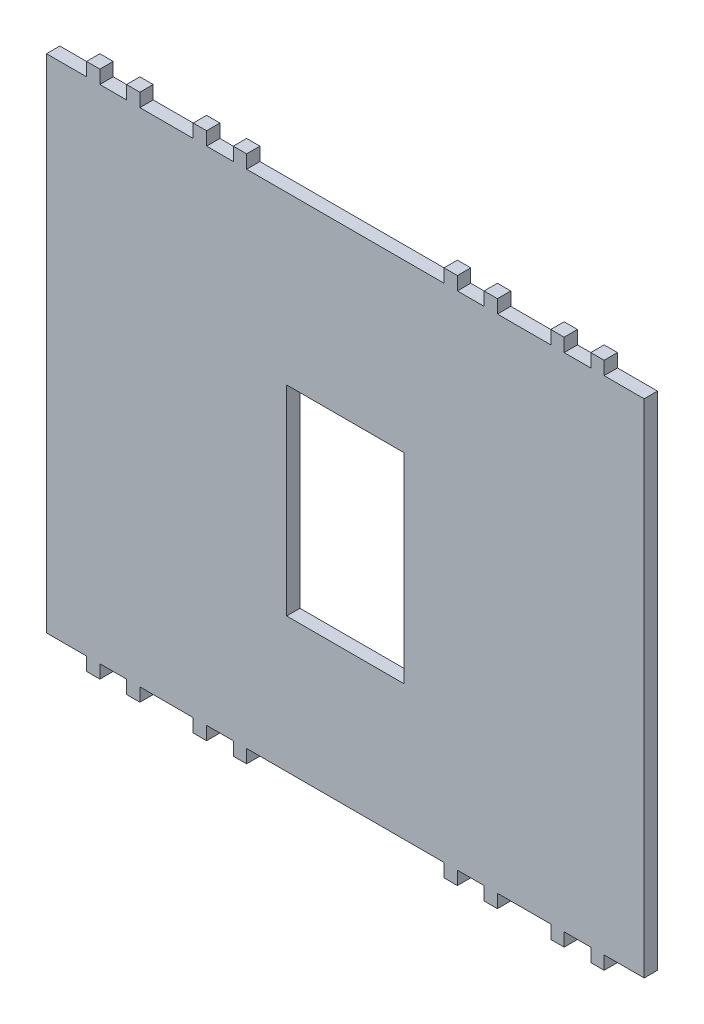
SolidWorks part; units mm, degrees
ref_plane "Plan de face" through (0, 0, 0) normal (0, 0, 1) x (1, 0, 0)
ref_plane "Plan de dessus" through (0, 0, 0) normal (0, 1, 0) x (1, 0, 0)
ref_plane "Plan de droite" through (0, 0, 0) normal (1, 0, 0) x (0, 0, -1)
sketch "Esquisse1" plane through (0, 0, 0) normal (0, 0, 1) x (1, 0, 0)
  line L0 (0, 0) -> (0, 94) construction
  line L1 (-21.3539, 94) -> (28.0805, 94) construction
  line L2 (-30, 188) -> (-45, 188)
  line L3 (-45, 188) -> (-45, 0) construction
  line L4 (-45, 0) -> (-30, 0)
  line L5 (-10, 0) -> (10, 0)
  line L6 (30, 0) -> (45, 0)
  line L7 (45, 0) -> (45, 188)
  line L8 (45, 188) -> (30, 188)
  line L9 (10, 188) -> (-10, 188)
  line L10 (-45, 188) -> (-45, 125.5) construction
  line L11 (-45, 125.5) -> (-89, 125.5)
  line L12 (-67, 125.5) -> (-67, 50.5) construction
  line L13 (-67, 50.5) -> (-45, 50.5)
  line L14 (-45, 50.5) -> (-45, 0) construction
  line L15 (-67, 50.5) -> (-89, 50.5)
  line L16 (-89, 50.5) -> (-89, 0) construction
  line L17 (-89, 0) -> (-104, 0)
  line L18 (-124, 0) -> (-144, 0)
  line L19 (-164, 0) -> (-179, 0)
  line L20 (-179, 0) -> (-179, 188)
  line L21 (-179, 188) -> (-164, 188)
  line L22 (-144, 188) -> (-124, 188)
  line L23 (-89, 188) -> (-89, 125.5) construction
  line L24 (-104, 188) -> (-89, 188)
  line L25 (-179, 0) -> (-179, 188) construction
  line L26 (-179, 0) -> (-174, 0) construction
  line L27 (-89, 125.5) -> (-89, 50.5)
  line L28 (-45, 50.5) -> (-45, 125.5)
  line L29 (-89, 188) -> (-45, 188)
  line L30 (-89, 0) -> (-45, 0)
  line B0 (-20, 0) -> (-20, 11.1075) construction
  line B1 (-20, 0) -> (-25, 0)
  line B2 (-25, -5) -> (-30, -5)
  line B3 (-30, -5) -> (-30, 0)
  line B4 (-25, -5) -> (-25, 0)
  line B5 (-20, 0) -> (-15, 0)
  line B6 (-15, 0) -> (-15, -5)
  line B7 (-15, -5) -> (-10, -5)
  line B8 (-10, -5) -> (-10, 0)
  line B9 (20, 0) -> (20, 11.1075) construction
  line B10 (20, 0) -> (25, 0)
  line B11 (25, -5) -> (30, -5)
  line B12 (30, -5) -> (30, 0)
  line B13 (25, -5) -> (25, 0)
  line B14 (20, 0) -> (15, 0)
  line B15 (15, 0) -> (15, -5)
  line B16 (15, -5) -> (10, -5)
  line B17 (10, -5) -> (10, 0)
  line B18 (20, 188) -> (20, 176.8925) construction
  line B19 (20, 188) -> (25, 188)
  line B20 (25, 193) -> (30, 193)
  line B21 (30, 193) -> (30, 188)
  line B22 (25, 193) -> (25, 188)
  line B23 (20, 188) -> (15, 188)
  line B24 (15, 188) -> (15, 193)
  line B25 (15, 193) -> (10, 193)
  line B26 (10, 193) -> (10, 188)
  line B27 (-20, 188) -> (-20, 176.8925) construction
  line B28 (-20, 188) -> (-25, 188)
  line B29 (-25, 193) -> (-30, 193)
  line B30 (-30, 193) -> (-30, 188)
  line B31 (-25, 193) -> (-25, 188)
  line B32 (-20, 188) -> (-15, 188)
  line B33 (-15, 188) -> (-15, 193)
  line B34 (-15, 193) -> (-10, 193)
  line B35 (-10, 193) -> (-10, 188)
  line B36 (-114, 0) -> (-114, 11.1075) construction
  line B37 (-114, 0) -> (-109, 0)
  line B38 (-109, -5) -> (-104, -5)
  line B39 (-104, -5) -> (-104, 0)
  line B40 (-109, -5) -> (-109, 0)
  line B41 (-114, 0) -> (-119, 0)
  line B42 (-119, 0) -> (-119, -5)
  line B43 (-119, -5) -> (-124, -5)
  line B44 (-124, -5) -> (-124, 0)
  line B45 (-154, 0) -> (-154, 11.1075) construction
  line B46 (-154, 0) -> (-159, 0)
  line B47 (-159, -5) -> (-164, -5)
  line B48 (-164, -5) -> (-164, 0)
  line B49 (-159, -5) -> (-159, 0)
  line B50 (-154, 0) -> (-149, 0)
  line B51 (-149, 0) -> (-149, -5)
  line B52 (-149, -5) -> (-144, -5)
  line B53 (-144, -5) -> (-144, 0)
  line B54 (-154, 188) -> (-154, 176.8925) construction
  line B55 (-154, 188) -> (-159, 188)
  line B56 (-159, 193) -> (-164, 193)
  line B57 (-164, 193) -> (-164, 188)
  line B58 (-159, 193) -> (-159, 188)
  line B59 (-154, 188) -> (-149, 188)
  line B60 (-149, 188) -> (-149, 193)
  line B61 (-149, 193) -> (-144, 193)
  line B62 (-144, 193) -> (-144, 188)
  line B63 (-114, 188) -> (-114, 176.8925) construction
  line B64 (-114, 188) -> (-109, 188)
  line B65 (-109, 193) -> (-104, 193)
  line B66 (-104, 193) -> (-104, 188)
  line B67 (-109, 193) -> (-109, 188)
  line B68 (-114, 188) -> (-119, 188)
  line B69 (-119, 188) -> (-119, 193)
  line B70 (-119, 193) -> (-124, 193)
  line B71 (-124, 193) -> (-124, 188)
  dimension "D1" = 40
  dimension "D2" = 15
  dimension "D3" = 15
  dimension "D4" = 188
  dimension "D5" = 75
sketch_block_instance "Insert M3 plots ep 5mm-1"
sketch_block "Insert M3 plots ep 5mm" parameters "D1"=10, "D2"=5, "D3"=5
sketch_block_instance "Insert M3 plots ep 5mm-3"
sketch_block_instance "Insert M3 plots ep 5mm-4"
sketch_block_instance "Insert M3 plots ep 5mm-5"
sketch_block_instance "Insert M3 plots ep 5mm-6"
sketch_block_instance "Insert M3 plots ep 5mm-7"
sketch_block_instance "Insert M3 plots ep 5mm-8"
sketch_block_instance "Insert M3 plots ep 5mm-9"
extrude "Boss.-Extru.1" add sketch "Esquisse1" along normal blind 5 contours B35 B34 B33 B32 B28 B31 B29 B30 L2 L3 L4 B3 B2 B4 B1 B5 B6 B7 B8 L5 B17 B16 B15 B14 B10 B13 B11 B12 L6 L7 L8 B21 B20 B22 B19 B23 B24 B25 B26 L9
